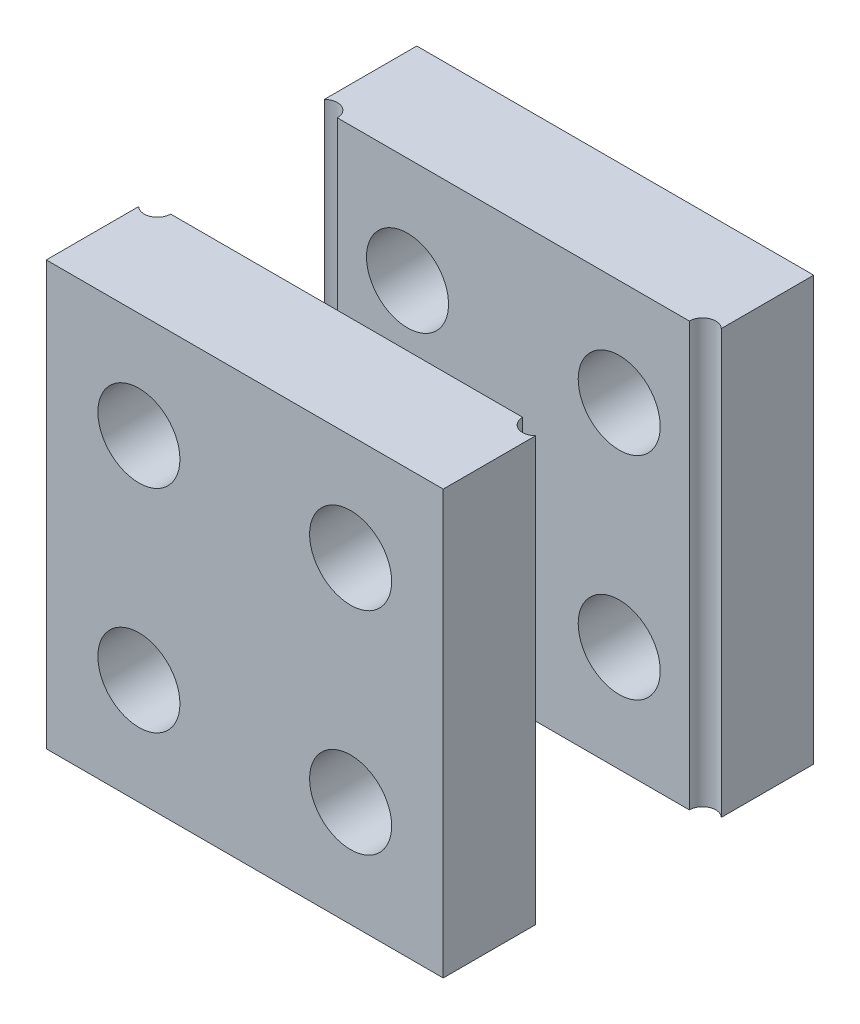
SolidWorks part; units mm, degrees
material "PLA"
ref_plane "前视基准面" through (0, 0, 0) normal (0, 0, 1) x (1, 0, 0)
ref_plane "上视基准面" through (0, 0, 0) normal (0, 1, 0) x (1, 0, 0)
ref_plane "右视基准面" through (0, 0, 0) normal (1, 0, 0) x (0, 0, -1)
sketch "草图1" plane through (0, 0, 0) normal (0, 0, 1) x (1, 0, 0)
  line L1 (7.5, -8) -> (-7.5, -8)
  line L2 (7.5, -8) -> (7.5, 8)
  line L3 (7.5, 8) -> (-7.5, 8)
  line L4 (-7.5, -8) -> (-7.5, 8)
  line L5 (0, 8) -> (0, -8) construction
  line L6 (7.5, 0) -> (-7.5, 0) construction
  circle A0 centre (-4, 4) radius 1.55
  circle A1 centre (4, 4) radius 1.55
  circle A2 centre (-4, -4) radius 1.55
  circle A3 centre (4, -4) radius 1.55
  point P0 (0, 0)
  dimension "D1" = 3.1
  dimension "D2" = 8
  dimension "D3" = 8
  dimension "D4" = 4
  dimension "D5" = 15
extrude "凸台-拉伸1" add sketch "草图1" along normal blind 14
sketch "草图2" plane through (0, 8, 0) normal (0, 1, 0) x (1, 0, 0)
  line L0 (0, 0) -> (0, -6.4514) construction
  line L1 (7.5, -7) -> (2.483, -7) construction
  line L2 (7.5, -14) -> (7.5, 0) construction
  line L4 (7.65, -10.15) -> (-7.65, -10.15)
  line L5 (7.65, -10.15) -> (7.65, -3.85)
  line L6 (7.65, -3.85) -> (-7.65, -3.85)
  line L7 (-7.65, -10.15) -> (-7.65, -3.85)
  line L8 (0, -3.85) -> (0, -10.15) construction
  line L9 (7.65, -7) -> (-7.65, -7) construction
  circle A0 centre (-7.15, -3.85) radius 0.5
  circle A1 centre (7.15, -3.85) radius 0.5
  circle A2 centre (7.15, -10.15) radius 0.5
  circle A3 centre (-7.15, -10.15) radius 0.5
  point P7 (0, -7)
  dimension "D3" = 1
  dimension "D1" = 15.3
  dimension "D2" = 6.3
extrude "切除-拉伸1" cut sketch "草图2" against normal through all and the other way through all contours L7 A3 L4 A2 L5 A1 L6 A0 | L6 A0 | L6 A0 | A3 L4 | A3 L4 | A1 L6 | A1 L6 | L4 A2 | L4 A2
